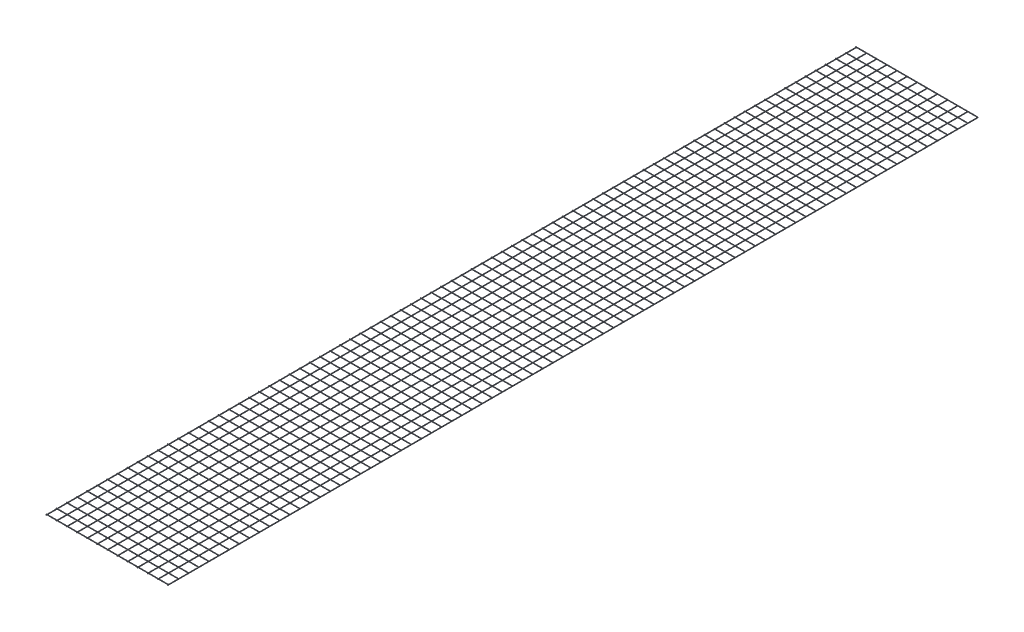
SolidWorks part; units mm, degrees
ref_plane "Front Plane" through (0, 0, 0) normal (0, 0, 1) x (1, 0, 0)
ref_plane "Top Plane" through (0, 0, 0) normal (0, 1, 0) x (1, 0, 0)
ref_plane "Right Plane" through (0, 0, 0) normal (1, 0, 0) x (0, 0, -1)
sketch "Sketch1" plane through (0, 0, 0) normal (0, 0, 1) x (1, 0, 0)
  line L0 (2.75, 0) -> (-2.75, 0) construction
  circle A0 centre (-77.2385, 0) radius 2.5
  circle A1 centre (22.7615, 0) radius 2.5
  circle A2 centre (122.7615, 0) radius 2.5
  circle A3 centre (222.7615, 0) radius 2.5
  circle A4 centre (322.7615, 0) radius 2.5
  circle A5 centre (422.7615, 0) radius 2.5
  circle A6 centre (522.7615, 0) radius 2.5
  circle A7 centre (622.7615, 0) radius 2.5
  circle A8 centre (722.7615, 0) radius 2.5
  circle A9 centre (822.7615, 0) radius 2.5
  circle A10 centre (922.7615, 0) radius 2.5
  circle A11 centre (1022.7615, 0) radius 2.5
  circle A12 centre (1122.7615, 0) radius 2.5
  dimension "D1" = 13
extrude "Boss-Extrude2" add sketch "Sketch1" along normal blind 8000
ref_plane "Plane1" through (-79.7385, 0, 0) normal (-1, 0, 0) x (0, 0, 1)
sketch "Sketch2" plane through (-79.7385, 0, 0) normal (-1, 0, 0) x (0, 0, 1)
  circle A0 centre (2.5, 5) radius 2.5
  circle A1 centre (102.44, 5) radius 2.5
  circle A2 centre (202.38, 5) radius 2.5
  circle A3 centre (302.32, 5) radius 2.5
  circle A4 centre (402.26, 5) radius 2.5
  circle A5 centre (502.2, 5) radius 2.5
  circle A6 centre (602.14, 5) radius 2.5
  circle A7 centre (702.08, 5) radius 2.5
  circle A8 centre (802.02, 5) radius 2.5
  circle A9 centre (901.96, 5) radius 2.5
  circle A10 centre (1001.9, 5) radius 2.5
  circle A11 centre (1101.84, 5) radius 2.5
  circle A12 centre (1201.78, 5) radius 2.5
  circle A13 centre (1301.72, 5) radius 2.5
  circle A14 centre (1401.66, 5) radius 2.5
  circle A15 centre (1501.6, 5) radius 2.5
  circle A16 centre (1601.54, 5) radius 2.5
  circle A17 centre (1701.48, 5) radius 2.5
  circle A18 centre (1801.42, 5) radius 2.5
  circle A19 centre (1901.36, 5) radius 2.5
  circle A20 centre (2001.3, 5) radius 2.5
  circle A21 centre (2101.24, 5) radius 2.5
  circle A22 centre (2201.18, 5) radius 2.5
  circle A23 centre (2301.12, 5) radius 2.5
  circle A24 centre (2401.06, 5) radius 2.5
  circle A25 centre (2501, 5) radius 2.5
  circle A26 centre (2600.94, 5) radius 2.5
  circle A27 centre (2700.88, 5) radius 2.5
  circle A28 centre (2800.82, 5) radius 2.5
  circle A29 centre (2900.76, 5) radius 2.5
  circle A30 centre (3000.7, 5) radius 2.5
  circle A31 centre (3100.64, 5) radius 2.5
  circle A32 centre (3200.58, 5) radius 2.5
  circle A33 centre (3300.52, 5) radius 2.5
  circle A34 centre (3400.46, 5) radius 2.5
  circle A35 centre (3500.4, 5) radius 2.5
  circle A36 centre (3600.34, 5) radius 2.5
  circle A37 centre (3700.28, 5) radius 2.5
  circle A38 centre (3800.22, 5) radius 2.5
  circle A39 centre (3900.16, 5) radius 2.5
  circle A40 centre (4000.1, 5) radius 2.5
  circle A41 centre (4100.04, 5) radius 2.5
  circle A42 centre (4199.98, 5) radius 2.5
  circle A43 centre (4299.92, 5) radius 2.5
  circle A44 centre (4399.86, 5) radius 2.5
  circle A45 centre (4499.8, 5) radius 2.5
  circle A46 centre (4599.74, 5) radius 2.5
  circle A47 centre (4699.68, 5) radius 2.5
  circle A48 centre (4799.62, 5) radius 2.5
  circle A49 centre (4899.56, 5) radius 2.5
  circle A50 centre (4999.5, 5) radius 2.5
  circle A51 centre (5099.44, 5) radius 2.5
  circle A52 centre (5199.38, 5) radius 2.5
  circle A53 centre (5299.32, 5) radius 2.5
  circle A54 centre (5399.26, 5) radius 2.5
  circle A55 centre (5499.2, 5) radius 2.5
  circle A56 centre (5599.14, 5) radius 2.5
  circle A57 centre (5699.08, 5) radius 2.5
  circle A58 centre (5799.02, 5) radius 2.5
  circle A59 centre (5898.96, 5) radius 2.5
  circle A60 centre (5998.9, 5) radius 2.5
  circle A61 centre (6098.84, 5) radius 2.5
  circle A62 centre (6198.78, 5) radius 2.5
  circle A63 centre (6298.72, 5) radius 2.5
  circle A64 centre (6398.66, 5) radius 2.5
  circle A65 centre (6498.6, 5) radius 2.5
  circle A66 centre (6598.54, 5) radius 2.5
  circle A67 centre (6698.48, 5) radius 2.5
  circle A68 centre (6798.42, 5) radius 2.5
  circle A69 centre (6898.36, 5) radius 2.5
  circle A70 centre (6998.3, 5) radius 2.5
  circle A71 centre (7098.24, 5) radius 2.5
  circle A72 centre (7198.18, 5) radius 2.5
  circle A73 centre (7298.12, 5) radius 2.5
  circle A74 centre (7398.06, 5) radius 2.5
  circle A75 centre (7498, 5) radius 2.5
  circle A76 centre (7597.94, 5) radius 2.5
  circle A77 centre (7697.88, 5) radius 2.5
  circle A78 centre (7797.82, 5) radius 2.5
  circle A79 centre (7897.76, 5) radius 2.5
  circle A80 centre (7997.7, 5) radius 2.5
  dimension "D1" = 81
extrude "Boss-Extrude3" add sketch "Sketch2" against normal blind 1205 separate body
